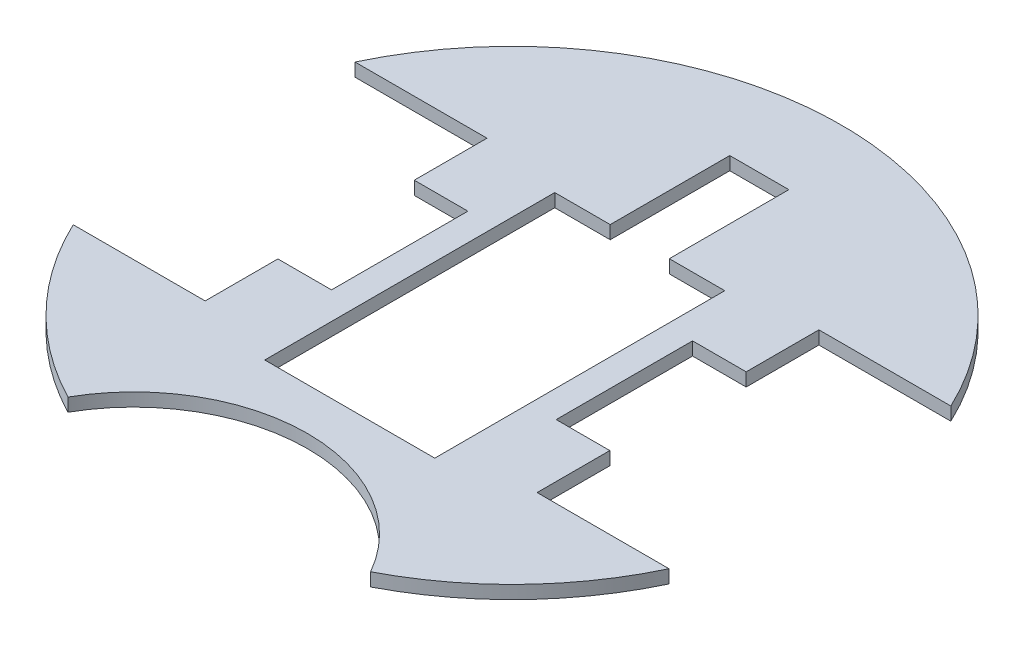
SolidWorks part; units mm, degrees
ref_plane "Front Plane" through (0, 0, 0) normal (0, 0, 1) x (1, 0, 0)
ref_plane "Top Plane" through (0, 0, 0) normal (0, 1, 0) x (1, 0, 0)
ref_plane "Right Plane" through (0, 0, 0) normal (1, 0, 0) x (0, 0, -1)
sketch "Sketch1" plane through (0, 0, 0) normal (0, 1, 0) x (1, 0, 0)
  line L0 (0, -83.2398) -> (-33.2911, -64.4046) construction
  line L1 (0, -83.2398) -> (0, 0) construction
  arc A0 (33.2911, -64.4046) -> (-33.2911, -64.4046) centre (0, 0) ccw
  arc A1 (33.2911, -64.4046) -> (-33.2911, -64.4046) centre (0, -83.2398) ccw
  dimension "D1" = 145
  dimension "D2" = 76.5
  dimension "D3" = 60.5
extrude "Boss-Extrude1" add sketch "Sketch1" along normal blind 2.9
sketch "solenoid placement" plane through (0, 2.9, 0) normal (0, 1, 0) x (1, 0, 0)
  line L4 (-18.7, -35.7) -> (18.7, -35.7)
  line L5 (18.7, -35.7) -> (18.7, 28.1)
  line L6 (18.7, 28.1) -> (-18.7, 28.1)
  line L7 (-18.7, 28.1) -> (-18.7, -35.7)
  line L8 (-18.7, -35.7) -> (18.7, -35.7)
  line L9 (18.7, -35.7) -> (18.7, 28.1)
  line L10 (18.7, 28.1) -> (-18.7, 28.1)
  line L11 (-18.7, 28.1) -> (-18.7, -35.7)
  circle A1 centre (0, 0) radius 72.5 construction
  arc A2 (33.2911, -64.4046) -> (-33.2911, -64.4046) centre (0, 0) ccw construction
  dimension "D1" = 0
extrude "Cut-Extrude1" cut sketch "solenoid placement" against normal through all
sketch "Sketch3" plane through (0, 2.9, 0) normal (0, 1, 0) x (1, 0, 0)
  line L0 (-36.51, -15) -> (-36.51, -31)
  line L1 (-24.71, 15) -> (-36.51, 15)
  line L2 (-24.71, 15) -> (-24.71, -15)
  line L3 (-24.71, -15) -> (-36.51, -15)
  line L4 (0, 0) -> (0, 72.5) construction
  line L5 (-36.51, -31) -> (-65.5382, -31)
  line L6 (-36.51, 15) -> (-36.51, 31)
  line L7 (-36.51, 31) -> (-65.5382, 31)
  line L8 (36.51, 31) -> (65.5382, 31)
  line L9 (36.51, 15) -> (36.51, 31)
  line L10 (36.51, -31) -> (65.5382, -31)
  line L11 (24.71, -15) -> (36.51, -15)
  line L12 (24.71, 15) -> (24.71, -15)
  line L13 (24.71, 15) -> (36.51, 15)
  line L14 (36.51, -15) -> (36.51, -31)
  arc A0 (33.2911, -64.4046) -> (-33.2911, -64.4046) centre (0, 0) ccw construction
  arc A1 (-65.5382, 31) -> (-65.5382, -31) centre (0, 0) ccw
  arc A2 (65.5382, 31) -> (65.5382, -31) centre (0, 0) cw
  dimension "D1" = 62
extrude "Cut-Extrude3" cut sketch "Sketch3" against normal through all
sketch "Sketch4" plane through (0, 2.9, 0) normal (0, 1, 0) x (1, 0, 0)
  line L1 (-6.5, 28.1) -> (6.5, 28.1)
  line L2 (-6.5, 28.1) -> (-6.5, 54.4)
  line L4 (6.5, 28.1) -> (6.5, 54.4)
  line L5 (6.5, 54.4) -> (-6.5, 54.4) construction
  line L6 (18.7, 28.1) -> (-18.7, 28.1) construction
  line L8 (6.5, 54.4) -> (-6.5, 54.4)
  point P6 (0, 28.1)
extrude "Cut-Extrude4" cut sketch "Sketch4" against normal through all
equation "\"smallPulleyTeeth\"= 15"
equation "\"largePulleyTeeth\"= 40"
equation "\"eighthThick\"= 2.9mm"
equation "\"sixteenthThick\" = 1.7mm"
equation "\"quarterThick\"=5.9mm"
equation "\"OD\" = 145mm"
equation "\"puckAngle\" = 60.5deg"
equation "\"D1@Sketch1\"=\"OD\""
equation "\"puckDiam\" = 76.5mm"
equation "\"D2@Sketch1\"=\"puckDiam\""
equation "\"D3@Sketch1\"=\"puckAngle\""
equation "\"D1@Boss-Extrude1\"=\"eighthThick\""
equation "\"axlePress\" = 5.9mm"
equation "\"press\" = 0.2mm"
equation "\"wheelClear\" = 0.3mm"
equation "\"10-32clear\" = 4.5mm"
equation "\"6-32clear\" = 3.3mm"
equation "\"8-32clear\" = 4.0mm"
equation "\"wheelHeight\" = 24mm"
equation "\"wheelWell\" = 62mm"
equation "\"D1@Sketch3\"=\"wheelWell\""
